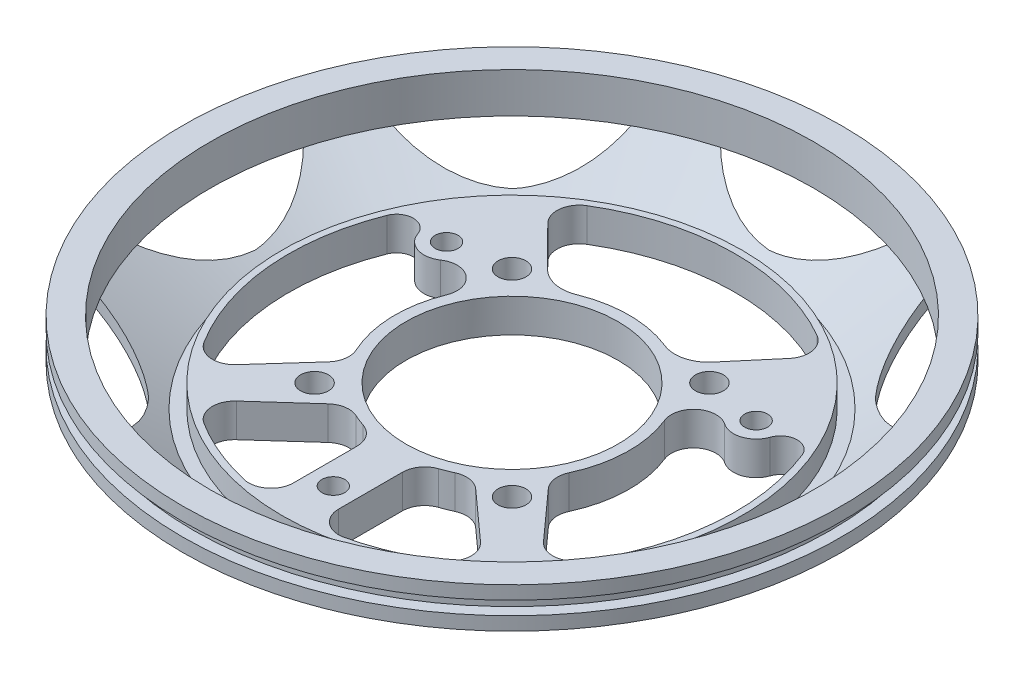
SolidWorks part; units mm, degrees
ref_plane "Front Plane" through (0, 0, 0) normal (0, 0, 1) x (1, 0, 0)
ref_plane "Top Plane" through (0, 0, 0) normal (0, 1, 0) x (1, 0, 0)
ref_plane "Right Plane" through (0, 0, 0) normal (1, 0, 0) x (0, 0, -1)
sketch "Sketch2" plane through (0, 0, 0) normal (1, 0, 0) x (0, 0, -1)
  line L1 (0, 0) -> (0, 17.0019) construction
  line L2 (-29.5, 0) -> (-29.5, -1.2)
  line L3 (-29.5, -1.2) -> (-28.5, -1.2)
  line L4 (-28.5, -1.2) -> (-28.5, -2.4)
  line L5 (-28.5, -2.4) -> (-29.5, -2.4)
  line L6 (-29.5, -2.4) -> (-29.5, -3.6)
  line L8 (0, -3.6) -> (0, 0) construction
  line L9 (-29.5, 0) -> (-27, 0)
  line L10 (-27, 0) -> (-27, -3.6)
  line L11 (-27, -3.6) -> (-29.5, -3.6)
  point P4 (0, 0)
  dimension "D1" = 29.5
  dimension "D2" = 1.2
  dimension "D3" = 1.2
  dimension "D4" = 1.2
  dimension "D5" = 1
  dimension "D6" = 1
  dimension "D7" = 2.5
revolve "Revolve1" add sketch "Sketch2" angle 360 about L1
sketch "Sketch4" plane through (0, 0, 0) normal (1, 0, 0) x (0, 0, -1)
  line L0 (-29.5, -3.6) -> (-22, -8.2)
  line L1 (0, 0) -> (0, -9.8561) construction
  line L2 (-22, -8.2) -> (0, -8.2)
  line L3 (-29.5, -3.6) -> (29.5, -3.6) construction
  line L4 (-23.762, -3.6) -> (-21.1533, -5.2)
  line L5 (-21.1533, -5.2) -> (0, -5.2)
  line L6 (-29.5, -3.6) -> (-23.762, -3.6)
  line L7 (0, -5.2) -> (0, -8.2)
  line L8 (-27.9315, -1.0427) -> (-21.1533, -5.2) construction
  dimension "D1" = 22
  dimension "D2" = 4.6
  dimension "D3" = 3
revolve "Revolve2" add sketch "Sketch4" angle 360 about L1
sketch "Sketch10" plane through (0, 0, 0) normal (1, 0, 0) x (0, 0, -1)
  line L0 (-29.5006, -3.6) -> (-22, -8.2) construction
  line L1 (-22, -8.2) -> (0, -8.2) construction
  line L6 (0, 0) -> (0, -23.3618) construction
  line L7 (29.5, -3.6) -> (-29.5, -3.6) construction
  line L8 (-27.5878, -3.6) -> (-21.7178, -7.2)
  line L9 (-21.7178, -7.2) -> (-20.5878, -7.2)
  line L10 (-27.5878, -3.6) -> (-20.5878, -3.6)
  line L11 (-20.5878, -3.6) -> (-20.5878, -7.2)
  line L12 (-28.9778, -2.7475) -> (-21.7178, -7.2) construction
  line L13 (-21.7178, -7.2) -> (0, -7.2) construction
  dimension "D1" = 22
  dimension "D2" = 4.6
  dimension "D3" = 1
  dimension "D4" = 7
  dimension "D5" = 1.13
revolve "Cut-Revolve1" cut sketch "Sketch10" angle 360 about L6
sketch "Sketch5" plane through (0, -8.2, 0) normal (0, -1, 0) x (1, 0, 0)
  line L0 (-9.15, -28.0451) -> (9.15, -28.0451) construction
  line L1 (-9.15, -28.0451) -> (-9.15, -31.0451)
  line L2 (9.15, -28.0451) -> (9.15, -31.0451)
  line L3 (9.15, -31.0451) -> (-9.15, -31.0451)
  line L4 (-15.4822, -28.4222) -> (-28.4222, -15.4822)
  line L5 (-26.3009, -13.3609) -> (-28.4222, -15.4822)
  line L6 (-13.3609, -26.3009) -> (-15.4822, -28.4222)
  line L7 (-31.0451, -9.15) -> (-31.0451, 9.15)
  line L8 (-28.0451, 9.15) -> (-31.0451, 9.15)
  line L9 (-28.0451, -9.15) -> (-31.0451, -9.15)
  line L10 (-28.4222, 15.4822) -> (-15.4822, 28.4222)
  line L11 (-13.3609, 26.3009) -> (-15.4822, 28.4222)
  line L12 (-26.3009, 13.3609) -> (-28.4222, 15.4822)
  line L13 (-9.15, 31.0451) -> (9.15, 31.0451)
  line L14 (9.15, 28.0451) -> (9.15, 31.0451)
  line L15 (-9.15, 28.0451) -> (-9.15, 31.0451)
  line L16 (15.4822, 28.4222) -> (28.4222, 15.4822)
  line L17 (26.3009, 13.3609) -> (28.4222, 15.4822)
  line L18 (13.3609, 26.3009) -> (15.4822, 28.4222)
  line L19 (31.0451, 9.15) -> (31.0451, -9.15)
  line L20 (28.0451, -9.15) -> (31.0451, -9.15)
  line L21 (28.0451, 9.15) -> (31.0451, 9.15)
  line L22 (28.4222, -15.4822) -> (15.4822, -28.4222)
  line L23 (13.3609, -26.3009) -> (15.4822, -28.4222)
  line L24 (26.3009, -13.3609) -> (28.4222, -15.4822)
  line L25 (0, 0) -> (0, 51.2012) construction
  line L26 (0, 0) -> (47.1012, 0) construction
  line L27 (0, 0) -> (-16.2635, 16.2635) construction
  circle A0 centre (0, 0) radius 29.5 construction
  arc A1 (-9.15, -28.0451) -> (0, -23) centre (0.6412, -34.9829) cw
  arc A2 (9.15, -28.0451) -> (0, -23) centre (-0.6412, -34.9829) ccw
  arc A3 (-26.3009, -13.3609) -> (-16.2635, -16.2635) centre (-24.2832, -25.19) cw
  arc A4 (-13.3609, -26.3009) -> (-16.2635, -16.2635) centre (-25.19, -24.2832) ccw
  arc A5 (-28.0451, 9.15) -> (-23, 0) centre (-34.9829, -0.6412) cw
  arc A6 (-28.0451, -9.15) -> (-23, 0) centre (-34.9829, 0.6412) ccw
  arc A7 (-13.3609, 26.3009) -> (-16.2635, 16.2635) centre (-25.19, 24.2832) cw
  arc A8 (-26.3009, 13.3609) -> (-16.2635, 16.2635) centre (-24.2832, 25.19) ccw
  arc A9 (9.15, 28.0451) -> (0, 23) centre (-0.6412, 34.9829) cw
  arc A10 (-9.15, 28.0451) -> (0, 23) centre (0.6412, 34.9829) ccw
  arc A11 (26.3009, 13.3609) -> (16.2635, 16.2635) centre (24.2832, 25.19) cw
  arc A12 (13.3609, 26.3009) -> (16.2635, 16.2635) centre (25.19, 24.2832) ccw
  arc A13 (28.0451, -9.15) -> (23, 0) centre (34.9829, 0.6412) cw
  arc A14 (28.0451, 9.15) -> (23, 0) centre (34.9829, -0.6412) ccw
  arc A15 (13.3609, -26.3009) -> (16.2635, -16.2635) centre (25.19, -24.2832) cw
  arc A16 (26.3009, -13.3609) -> (16.2635, -16.2635) centre (24.2832, -25.19) ccw
  circle A17 centre (0, 0) radius 9.5
  circle A18 centre (0, 0) radius 3 construction
  circle A19 centre (0, 0) radius 16 construction
  circle A20 centre (0, 0) radius 12.5 construction
  point P6 (0, -23)
  point P62 (0, 0)
  point P69 (0, 16)
  point P71 (13.8564, -8)
  point P72 (-8.8388, 8.8388)
  point P74 (-13.8564, -8)
  point P75 (0, 0)
  point P78 (8.8388, 8.8388)
  point P79 (8.8388, -8.8388)
  point P80 (-8.8388, -8.8388)
  point P81 (0, 0)
  dimension "D3" = 12
  dimension "D4" = 12
  dimension "D7" = 19
  dimension "D8" = 6
  dimension "D9" = 32
  dimension "D10" = 25
  dimension "D1" = 18.3
  dimension "D2" = 23
  dimension "D5" = 3
  dimension "D12" = 4
  dimension "D6" = 8
  dimension "D11" = 3
extrude "Cut-Extrude1" cut sketch "Sketch5" against normal blind 4.6
hole_wizard "M3x0.5 Tapped Hole1" positions "3DSketch1" profile "Sketch6" tap size "M3x0.5" standard "ANSI Metric" end condition through all
sketch3d "3DSketch1"
  point P0 (8.8388, -8.2, 8.8388)
  point P3 (-8.8388, -8.2, 8.8388)
  point P6 (-8.8388, -8.2, -8.8388)
  point P9 (8.8388, -8.2, -8.8388)
sketch "Sketch6" plane through (8.8388, -8.2, 8.8388) normal (1, 0, 0) x (0, 0, -1)
  line L0 (0, 0) -> (0, 8.2)
  line L1 (0, 8.2) -> (1.25, 8.2)
  line L2 (1.25, 8.2) -> (1.25, 0)
  line L5 (1.25, 0) -> (0, 0)
  line L11 (0, -6.35) -> (0, 107.95) construction
  dimension "Thru Tap Drill Dia." = 2.5
  dimension "Thru Tap Drill Depth" = 8.2
cosmetic thread "Hole Thread1" parameters "D2"=3
cosmetic thread "Hole Thread2" parameters "D2"=3
cosmetic thread "Hole Thread3" parameters "D2"=3
cosmetic thread "Hole Thread4" parameters "D2"=3
hole_wizard "M2.5x0.45 Tapped Hole1" positions "3DSketch2" profile "Sketch7" tap size "M2.5x0.45" standard "ANSI Metric" end condition through all
sketch3d "3DSketch2"
  point P0 (0, -8.2, 16)
  point P3 (-13.8564, -8.2, -8)
  point P6 (13.8564, -8.2, -8)
sketch "Sketch7" plane through (0, -8.2, 16) normal (1, 0, 0) x (0, 0, -1)
  line L0 (0, 0) -> (0, 8.2)
  line L1 (0, 8.2) -> (1.025, 8.2)
  line L2 (1.025, 8.2) -> (1.025, 0)
  line L5 (1.025, 0) -> (0, 0)
  line L11 (0, -6.35) -> (0, 107.95) construction
  dimension "Thru Tap Drill Dia." = 2.05
  dimension "Thru Tap Drill Depth" = 8.2
cosmetic thread "Hole Thread5" parameters "D2"=2.5
cosmetic thread "Hole Thread6" parameters "D2"=2.5
cosmetic thread "Hole Thread7" parameters "D2"=2.5
sketch "Sketch11" plane through (0, -8.2, 0) normal (0, -1, 0) x (1, 0, 0)
  line L0 (-7.21, -10.3917) -> (-10.7683, -13.9711)
  line L1 (7.3589, -10.5728) -> (10.517, -14.301)
  line L2 (-9.8518, 6.6012) -> (-13.7469, 10.9273)
  line L3 (0, 0) -> (-35.1854, 0) construction
  line L4 (-6.6012, 9.8518) -> (-10.9273, 13.7469)
  line L5 (0, 0) -> (0, 38.2204) construction
  line L6 (6.6012, 9.8518) -> (10.9273, 13.7469)
  line L7 (-2.025, 11.8342) -> (-2.025, 17.5442)
  line L8 (2.025, 11.8342) -> (2.025, 17.5442)
  line L9 (9.8518, 6.6012) -> (13.7469, 10.9273)
  arc A0 (-10.3888, -17.0902) -> (9.9899, -17.3263) centre (0, 0) ccw
  circle A1 centre (0, 0) radius 22 construction
  arc A2 (6.7272, -8.0619) -> (8.0619, -6.7272) centre (0, 0) ccw construction
  arc A3 (15.7697, -7.3367) -> (18.5805, -7.4004) centre (17.1869, -6.8454) ccw
  circle A4 centre (13.8564, -8) radius 2.025
  arc A5 (15.7697, -7.3367) -> (12.7185, -6.325) centre (13.8564, -8) ccw
  arc A6 (18.5805, -7.4004) -> (16.9258, 10.6544) centre (0, 0) ccw
  circle A7 centre (0, 16) radius 2.025
  circle A8 centre (0, 16) radius 2.025 construction
  arc A9 (-18.5805, -7.4004) -> (-15.7697, -7.3367) centre (-17.1869, -6.8454) ccw
  circle A10 centre (0, 0) radius 10.5
  arc A11 (-3.953, -9.7275) -> (3.9432, -9.7315) centre (0, 0) ccw
  arc A12 (7.3589, -10.5728) -> (3.9432, -9.7315) centre (5.0698, -12.5119) ccw
  arc A13 (-3.953, -9.7275) -> (-7.21, -10.3917) centre (-5.0824, -12.5068) ccw
  arc A14 (10.517, -14.301) -> (9.9899, -17.3263) centre (8.9909, -15.5937) cw
  arc A15 (-10.3888, -17.0902) -> (-10.7683, -13.9711) centre (-9.3499, -15.3811) cw
  arc A16 (-3.381, 9.9408) -> (-4.4209, 9.524) centre (0, 0) ccw
  arc A17 (-4.4722, 19.4936) -> (-10.6544, 16.9258) centre (0, 0) ccw
  arc A18 (10.6544, 16.9258) -> (4.4722, 19.4936) centre (0, 0) ccw
  arc A19 (4.4209, 9.524) -> (3.381, 9.9408) centre (0, 0) ccw
  arc A20 (-16.9258, 10.6544) -> (-18.5805, -7.4004) centre (0, 0) ccw
  arc A21 (10.9273, 13.7469) -> (10.6544, 16.9258) centre (9.589, 15.2332) ccw
  arc A22 (-9.524, 4.4209) -> (-9.7395, -3.9233) centre (0, 0) ccw
  arc A23 (4.4722, 19.4936) -> (2.025, 17.5442) centre (4.025, 17.5442) ccw
  arc A24 (-2.025, 17.5442) -> (-4.4722, 19.4936) centre (-4.025, 17.5442) ccw
  arc A25 (-10.6544, 16.9258) -> (-10.9273, 13.7469) centre (-9.589, 15.2332) ccw
  arc A26 (4.4209, 9.524) -> (6.6012, 9.8518) centre (5.263, 11.338) ccw
  arc A27 (3.381, 9.9408) -> (2.025, 11.8342) centre (4.025, 11.8342) cw
  arc A28 (-2.025, 11.8342) -> (-3.381, 9.9408) centre (-4.025, 11.8342) cw
  arc A29 (-4.4209, 9.524) -> (-6.6012, 9.8518) centre (-5.263, 11.338) cw
  arc A30 (-12.7185, -6.325) -> (-9.7395, -3.9233) centre (-11.5946, -4.6706) ccw
  arc A31 (-9.524, 4.4209) -> (-9.8518, 6.6012) centre (-11.338, 5.263) ccw
  arc A32 (-13.7469, 10.9273) -> (-16.9258, 10.6544) centre (-15.2332, 9.589) ccw
  arc A33 (9.7395, -3.9233) -> (12.7185, -6.325) centre (11.5946, -4.6706) ccw
  arc A34 (9.7395, -3.9233) -> (9.524, 4.4209) centre (0, 0) ccw
  arc A35 (9.524, 4.4209) -> (9.8518, 6.6012) centre (11.338, 5.263) cw
  arc A36 (16.9258, 10.6544) -> (13.7469, 10.9273) centre (15.2332, 9.589) ccw
  circle A402 centre (-13.8564, -8) radius 2.025
  arc A403 (-12.7185, -6.325) -> (-15.7697, -7.3367) centre (-13.8564, -8) ccw
  circle A405 centre (-8.8388, -8.8388) radius 2.25
  circle A406 centre (-8.8388, -8.8388) radius 2.25 construction
  circle A408 centre (-8.8388, 8.8388) radius 2.25
  circle A409 centre (-8.8388, 8.8388) radius 2.25 construction
  circle A411 centre (8.8388, 8.8388) radius 2.25
  circle A412 centre (8.8388, 8.8388) radius 2.25 construction
  circle A414 centre (8.8388, -8.8388) radius 2.25
  circle A415 centre (8.8388, -8.8388) radius 2.25 construction
  point P38 (5.811, -8.7454)
  point P41 (-5.6669, -8.8395)
  point P44 (11.9732, -16.0201)
  point P47 (-12.4442, -15.657)
  point P66 (12.7621, 15.399)
  point P71 (-2.025, 19.8972)
  point P74 (-12.7621, 15.399)
  point P77 (5.5553, 8.91)
  point P82 (-2.025, 10.3029)
  point P85 (-5.5553, 8.91)
  point P91 (-8.91, 5.5553)
  point P94 (-15.399, 12.7621)
  dimension "D1" = 2
  dimension "D10" = 3
  dimension "D11" = 9.6131
  dimension "D13" = 3
  dimension "D14" = 3
  dimension "D15" = 2
  dimension "D20" = 2
  dimension "D21" = 2
  dimension "D22" = 4
  dimension "D23" = 2
  dimension "D24" = 4
  dimension "D25" = 2
  dimension "D12" = 9.5338
  dimension "D16" = 48
  dimension "D17" = 48
  dimension "D18" = 48
  dimension "D19" = 48
  dimension "D2" = 1
  dimension "D3" = 1
  dimension "D4" = 1
  dimension "D5" = 1
  dimension "D6" = 1
  dimension "D7" = 1
  dimension "D8" = 1
  dimension "D9" = 1
extrude "Cut-Extrude2" cut sketch "Sketch11" against normal blind 4.6
